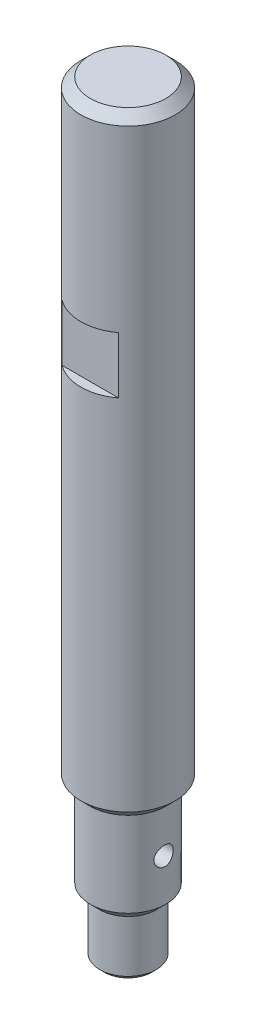
SolidWorks part; units mm, degrees
material "Простая углеродистая сталь"
ref_plane "Спереди" through (0, 0, 0) normal (0, 0, 1) x (1, 0, 0)
ref_plane "Сверху" through (0, 0, 0) normal (0, 1, 0) x (1, 0, 0)
ref_plane "Справа" through (0, 0, 0) normal (1, 0, 0) x (0, 0, -1)
sketch "Эскиз1" plane through (0, 0, 0) normal (0, 0, 1) x (1, 0, 0)
  line L0 (0, 0) -> (0, 232.1951) construction
  line L1 (-6, 1) -> (-5, 0)
  line L2 (-8, 14) -> (-8, 32)
  line L3 (-8, 32) -> (-10, 34)
  line L4 (-10, 34) -> (-10, 160)
  line L5 (-8, 162) -> (0, 162)
  line L6 (0, 162) -> (0, 0)
  line L7 (-10, 160) -> (-8, 162)
  line L8 (-6, 12) -> (-8, 14)
  line L9 (-6, 12) -> (-6, 1)
  line L10 (-5, 0) -> (0, 0)
  point P7 (-10, 162)
  point P13 (-6, 0)
  dimension "D1" = 128
  dimension "D2" = 20
  dimension "D3" = 2
  dimension "D4" = 45
  dimension "D5" = 16
  dimension "D6" = 45
  dimension "D7" = 12
  dimension "D8" = 20
  dimension "D9" = 45
  dimension "D10" = 14
  dimension "D11" = 1
  dimension "D12" = 45
revolve "Повернуть1" add sketch "Эскиз1" angle 360 about L0
sketch "Эскиз2" plane through (0, 162, 0) normal (0, 1, 0) x (1, 0, 0)
  line L1 (-10, -8) -> (10, -8)
  line L2 (-10, -8) -> (-10, 8)
  line L3 (-10, 8) -> (10, 8)
  line L4 (10, -8) -> (10, 8)
  line L5 (-10, -8) -> (10, 8) construction
  line L6 (-10, 8) -> (10, -8) construction
  circle A0 centre (0, 0) radius 10 construction
  point P0 (0, 0)
  dimension "D1" = 16
extrude "Вырез-Вытянуть1" cut sketch "Эскиз2" against normal blind 12 from offset 40 flip side to cut offset against normal yes
extrude "Вырез-Вытянуть2" cut sketch "Эскиз3" against normal through all both and the other way through all
sketch "Эскиз3" plane through (0, -33, 0) normal (0.9996, 0, 0.0276) x (0.0276, 0, -0.9996)
  circle A0 centre (0, 56) radius 2
